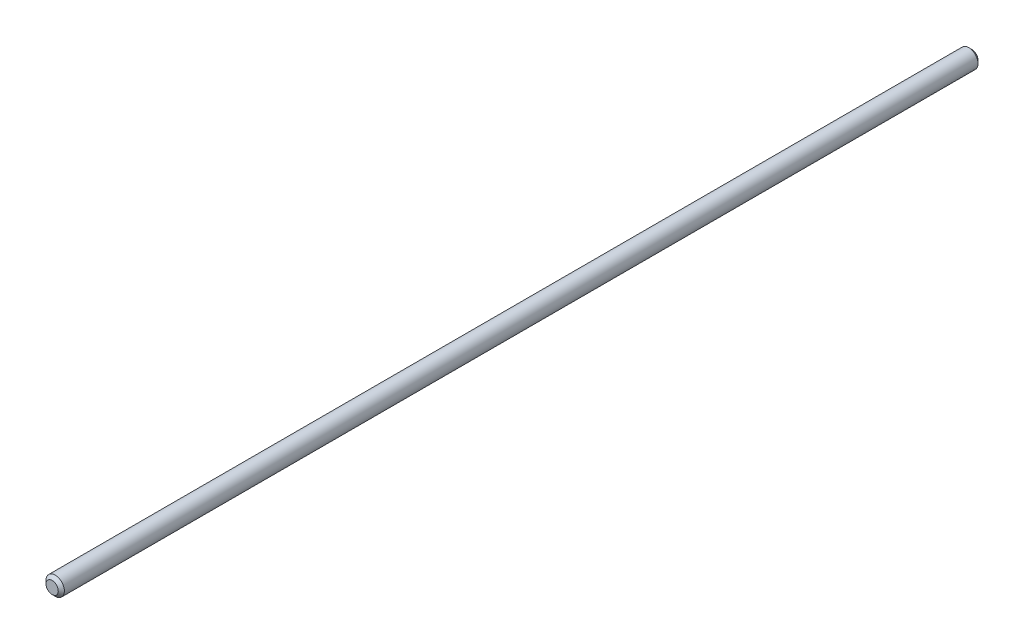
SolidWorks part; units mm, degrees
material "Stainless Steel (ferritic)"
ref_plane "Front Plane" through (0, 0, 0) normal (0, 0, 1) x (1, 0, 0)
ref_plane "Top Plane" through (0, 0, 0) normal (0, 1, 0) x (1, 0, 0)
ref_plane "Right Plane" through (0, 0, 0) normal (1, 0, 0) x (0, 0, -1)
sketch "Sketch1" plane through (0, 0, 0) normal (0, 0, 1) x (1, 0, 0)
  circle A0 centre (0, 0) radius 1.5
  dimension "D1" = 3
extrude "Boss-Extrude1" add sketch "Sketch1" along normal blind 150
chamfer "Chamfer1" distance 0.5 angle 45 2 edges at (1.5, 0, 0) (1.5, 0, 150)
